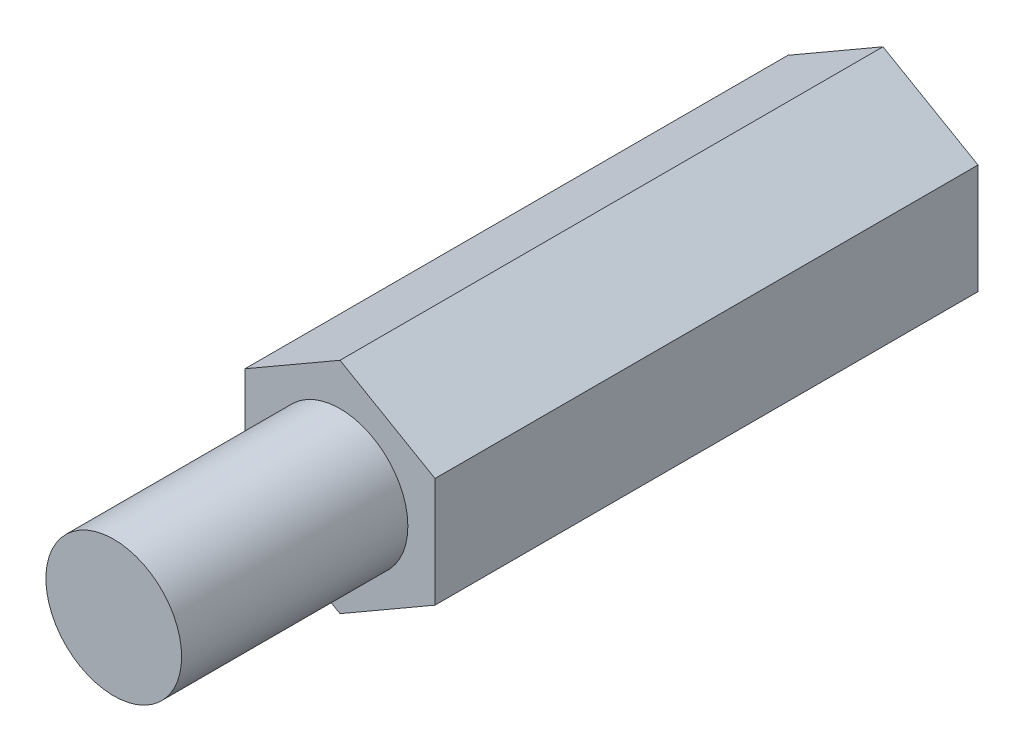
SolidWorks part; units mm, degrees
ref_plane "前视基准面" through (0, 0, 0) normal (0, 0, 1) x (1, 0, 0)
ref_plane "上视基准面" through (0, 0, 0) normal (0, 1, 0) x (1, 0, 0)
ref_plane "右视基准面" through (0, 0, 0) normal (1, 0, 0) x (0, 0, -1)
sketch "草图1" plane through (0, 0, 0) normal (0, 0, 1) x (1, 0, 0)
  line L1 (0, 2.4249) -> (-2.1, 1.2124)
  line L2 (-2.1, 1.2124) -> (-2.1, -1.2124)
  line L3 (-2.1, -1.2124) -> (0, -2.4249)
  line L4 (0, -2.4249) -> (2.1, -1.2124)
  line L5 (2.1, -1.2124) -> (2.1, 1.2124)
  line L6 (2.1, 1.2124) -> (0, 2.4249)
  circle A0 centre (0, 0) radius 2.1 construction
  circle A1 centre (0, 0) radius 1.5
  dimension "D1" = 4.2
extrude "凸台-拉伸1" add sketch "草图1" along normal blind 10
sketch "草图2" plane through (0, 0, 10) normal (0, 0, 1) x (1, 0, 0)
  line L6 (2.1, 1.2124) -> (0, 2.4249)
  line L7 (0, 2.4249) -> (-2.1, 1.2124)
  line L8 (-2.1, 1.2124) -> (-2.1, -1.2124)
  line L9 (-2.1, -1.2124) -> (0, -2.4249)
  line L10 (0, -2.4249) -> (2.1, -1.2124)
  line L11 (2.1, -1.2124) -> (2.1, 1.2124)
  line L12 (2.1, 1.2124) -> (0, 2.4249)
  line L13 (0, 2.4249) -> (-2.1, 1.2124)
  line L14 (-2.1, 1.2124) -> (-2.1, -1.2124)
  line L15 (-2.1, -1.2124) -> (0, -2.4249)
  line L16 (0, -2.4249) -> (2.1, -1.2124)
  line L17 (2.1, -1.2124) -> (2.1, 1.2124)
  dimension "D1" = 0
extrude "凸台-拉伸2" add sketch "草图2" along normal blind 2
sketch "草图3" plane through (0, 0, 12) normal (0, 0, 1) x (1, 0, 0)
  circle A0 centre (0, 0) radius 1.5
extrude "凸台-拉伸3" add sketch "草图3" along normal blind 5
